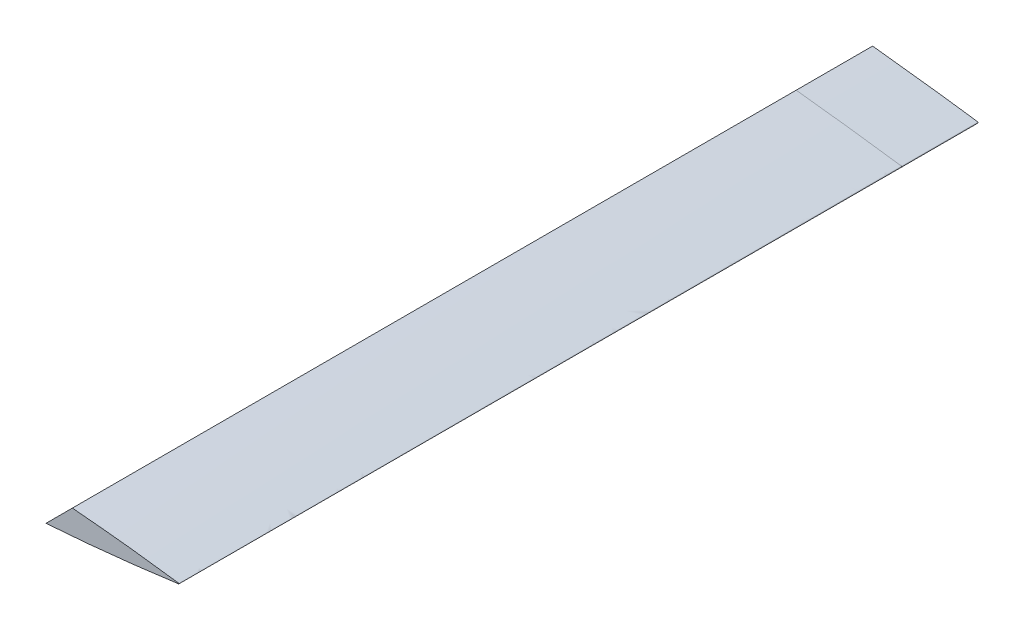
SolidWorks part; units mm, degrees
ref_plane "Front Plane" through (0, 0, 0) normal (1, 0, 0) x (0, 1, 0)
ref_plane "Top Plane" through (0, 0, 0) normal (0, 0, 1) x (0, 1, 0)
ref_plane "Right Plane" through (0, 0, 0) normal (0, 1, 0) x (-1, 0, 0)
curve "Curve2"
  spline degree 3 poles (90, 0.1134, 0) (89.9538, 0.1199, 0) (89.7691, 0.1458, 0) (89.3547, 0.2036, 0) (88.6668, 0.299, 0) (87.7097, 0.43, 0) (86.4894, 0.595, 0) (85.0132, 0.7907, 0) (83.2903, 1.0144, 0) (81.3314, 1.2627, 0) (79.1484, 1.5322, 0) (76.7549, 1.8188, 0) (74.1657, 2.1193, 0) (71.3966, 2.4294, 0) (68.4648, 2.7453, 0) (65.3883, 3.0632, 0) (62.1861, 3.379, 0) (58.878, 3.6881, 0) (55.4843, 3.9866, 0) (52.026, 4.2695, 0) (48.5244, 4.5321, 0) (45.001, 4.7696, 0) (41.4775, 4.977, 0) (37.9757, 5.149, 0) (34.5172, 5.2811, 0) (31.1233, 5.369, 0) (27.8148, 5.4084, 0) (24.6121, 5.3961, 0) (21.5349, 5.3298, 0) (18.6023, 5.2078, 0) (15.8322, 5.0298, 0) (13.2417, 4.7963, 0) (10.8466, 4.5092, 0) (8.6616, 4.1708, 0) (6.6998, 3.7847, 0) (4.9728, 3.3553, 0) (3.4903, 2.8868, 0) (2.26, 2.3835, 0) (1.2857, 1.8489, 0) (0.569, 1.2818, 0) (0.1099, 0.6686, 0) (-0.0512, 0, 0) (0.1099, -0.6686, 0) (0.569, -1.2818, 0) (1.2857, -1.8489, 0) (2.26, -2.3835, 0) (3.4903, -2.8868, 0) (4.9728, -3.3553, 0) (6.6998, -3.7847, 0) (8.6616, -4.1708, 0) (10.8466, -4.5092, 0) (13.2417, -4.7963, 0) (15.8322, -5.0298, 0) (18.6023, -5.2078, 0) (21.5349, -5.3298, 0) (24.6121, -5.3961, 0) (27.8148, -5.4084, 0) (31.1233, -5.369, 0) (34.5172, -5.2811, 0) (37.9757, -5.149, 0) (41.4775, -4.977, 0) (45.001, -4.7696, 0) (48.5244, -4.5321, 0) (52.026, -4.2695, 0) (55.4843, -3.9866, 0) (58.878, -3.6881, 0) (62.1861, -3.379, 0) (65.3883, -3.0632, 0) (68.4648, -2.7453, 0) (71.3966, -2.4294, 0) (74.1657, -2.1193, 0) (76.7549, -1.8188, 0) (79.1484, -1.5322, 0) (81.3314, -1.2627, 0) (83.2903, -1.0144, 0) (85.0132, -0.7907, 0) (86.4894, -0.595, 0) (87.7097, -0.43, 0) (88.6668, -0.299, 0) (89.3547, -0.2036, 0) (89.7691, -0.1458, 0) (89.9538, -0.1199, 0) (90, -0.1134, 0) knots 0 0 0 0 0.000763 0.003048 0.006841 0.012116 0.018841 0.026973 0.03646 0.047243 0.059254 0.072417 0.086651 0.101866 0.117969 0.134858 0.152428 0.170572 0.189175 0.208122 0.227297 0.24658 0.265853 0.284997 0.303895 0.322433 0.340499 0.357984 0.374788 0.390812 0.405965 0.420162 0.433328 0.445394 0.456301 0.466004 0.474472 0.481696 0.487704 0.492583 0.496544 0.5 0.503456 0.507417 0.512296 0.518304 0.525528 0.533996 0.543699 0.554606 0.566672 0.579838 0.594035 0.609188 0.625212 0.642016 0.659501 0.677567 0.696105 0.715003 0.734147 0.75342 0.772703 0.791878 0.810825 0.829428 0.847572 0.865142 0.882031 0.898134 0.913349 0.927583 0.940746 0.952757 0.96354 0.973027 0.981159 0.987884 0.993159 0.996952 0.999237 1 1 1 1
sketch "Sketch2" plane through (0, 0, 0) normal (0, 0, 1) x (0, 1, 0)
  arc A0 (-0.1134, -90) -> (0.1134, -90) centre (0, -89.9841) ccw
  spline S0 degree 3 poles (1966.8421, -449.5678) (-10.9329, -144.6657) (-3.7009, -117.3601) (0.2036, -89.3547) (0.299, -88.6668) (0.43, -87.7097) (0.595, -86.4894) (0.7907, -85.0132) (1.0144, -83.2903) (1.2627, -81.3314) (1.5322, -79.1484) (1.8188, -76.7549) (2.1193, -74.1657) (2.4294, -71.3966) (2.7453, -68.4648) (3.0632, -65.3883) (3.379, -62.1861) (3.6881, -58.878) (3.9866, -55.4843) (4.2695, -52.026) (4.5321, -48.5244) (4.7696, -45.001) (4.977, -41.4775) (5.149, -37.9757) (5.2811, -34.5172) (5.369, -31.1233) (5.4084, -27.8148) (5.3961, -24.6121) (5.3298, -21.5349) (5.2078, -18.6023) (5.0298, -15.8322) (4.7963, -13.2417) (4.5092, -10.8466) (4.1708, -8.6616) (3.7847, -6.6998) (3.3553, -4.9728) (2.8868, -3.4903) (2.3835, -2.26) (1.8489, -1.2857) (1.2818, -0.569) (0.6686, -0.1099) (0, 0.0512) (-0.6686, -0.1099) (-1.2818, -0.569) (-1.8489, -1.2857) (-2.3835, -2.26) (-2.8868, -3.4903) (-3.3553, -4.9728) (-3.7847, -6.6998) (-4.1708, -8.6616) (-4.5092, -10.8466) (-4.7963, -13.2417) (-5.0298, -15.8322) (-5.2078, -18.6023) (-5.3298, -21.5349) (-5.3961, -24.6121) (-5.4084, -27.8148) (-5.369, -31.1233) (-5.2811, -34.5172) (-5.149, -37.9757) (-4.977, -41.4775) (-4.7696, -45.001) (-4.5321, -48.5244) (-4.2695, -52.026) (-3.9866, -55.4843) (-3.6881, -58.878) (-3.379, -62.1861) (-3.0632, -65.3883) (-2.7453, -68.4648) (-2.4294, -71.3966) (-2.1193, -74.1657) (-1.8188, -76.7549) (-1.5322, -79.1484) (-1.2627, -81.3314) (-1.0144, -83.2903) (-0.7907, -85.0132) (-0.595, -86.4894) (-0.43, -87.7097) (-0.299, -88.6668) (-0.2036, -89.3547) (3.7009, -117.36) (10.9329, -144.6654) (-1966.8144, -449.5636) knots -0.45542 -0.45542 -0.45542 -0.45542 0.000763 0.003048 0.006841 0.012116 0.018841 0.026973 0.03646 0.047243 0.059254 0.072417 0.086651 0.101866 0.117969 0.134858 0.152428 0.170572 0.189175 0.208122 0.227297 0.24658 0.265853 0.284997 0.303895 0.322433 0.340499 0.357984 0.374788 0.390812 0.405965 0.420162 0.433328 0.445394 0.456301 0.466004 0.474472 0.481696 0.487704 0.492583 0.496544 0.5 0.503456 0.507417 0.512296 0.518304 0.525528 0.533996 0.543699 0.554606 0.566672 0.579838 0.594035 0.609188 0.625212 0.642016 0.659501 0.677567 0.696105 0.715003 0.734147 0.75342 0.772703 0.791878 0.810825 0.829428 0.847572 0.865142 0.882031 0.898134 0.913349 0.927583 0.940746 0.952757 0.96354 0.973027 0.981159 0.987884 0.993159 0.996952 0.999237 1.455418 1.455418 1.455418 1.455418 only from (0.1134, -90) to (-0.1134, -90) construction
  spline S1 degree 3 poles (0.1134, -90) (0.1199, -89.9538) (0.1458, -89.7691) (0.2036, -89.3547) (0.299, -88.6668) (0.43, -87.7097) (0.595, -86.4894) (0.7907, -85.0132) (1.0144, -83.2903) (1.2627, -81.3314) (1.5322, -79.1484) (1.8188, -76.7549) (2.1193, -74.1657) (2.4294, -71.3966) (2.7453, -68.4648) (3.0632, -65.3883) (3.379, -62.1861) (3.6881, -58.878) (3.9866, -55.4843) (4.2695, -52.026) (4.5321, -48.5244) (4.7696, -45.001) (4.977, -41.4775) (5.149, -37.9757) (5.2811, -34.5172) (5.369, -31.1233) (5.4084, -27.8148) (5.3961, -24.6121) (5.3298, -21.5349) (5.2078, -18.6023) (5.0298, -15.8322) (4.7963, -13.2417) (4.5092, -10.8466) (4.1708, -8.6616) (3.7847, -6.6998) (3.3553, -4.9728) (2.8868, -3.4903) (2.3835, -2.26) (1.8489, -1.2857) (1.2818, -0.569) (0.6686, -0.1099) (0, 0.0512) (-0.6686, -0.1099) (-1.2818, -0.569) (-1.8489, -1.2857) (-2.3835, -2.26) (-2.8868, -3.4903) (-3.3553, -4.9728) (-3.7847, -6.6998) (-4.1708, -8.6616) (-4.5092, -10.8466) (-4.7963, -13.2417) (-5.0298, -15.8322) (-5.2078, -18.6023) (-5.3298, -21.5349) (-5.3961, -24.6121) (-5.4084, -27.8148) (-5.369, -31.1233) (-5.2811, -34.5172) (-5.149, -37.9757) (-4.977, -41.4775) (-4.7696, -45.001) (-4.5321, -48.5244) (-4.2695, -52.026) (-3.9866, -55.4843) (-3.6881, -58.878) (-3.379, -62.1861) (-3.0632, -65.3883) (-2.7453, -68.4648) (-2.4294, -71.3966) (-2.1193, -74.1657) (-1.8188, -76.7549) (-1.5322, -79.1484) (-1.2627, -81.3314) (-1.0144, -83.2903) (-0.7907, -85.0132) (-0.595, -86.4894) (-0.43, -87.7097) (-0.299, -88.6668) (-0.2036, -89.3547) (-0.1458, -89.7691) (-0.1199, -89.9538) (-0.1134, -90) knots 0 0 0 0 0.000763 0.003048 0.006841 0.012116 0.018841 0.026973 0.03646 0.047243 0.059254 0.072417 0.086651 0.101866 0.117969 0.134858 0.152428 0.170572 0.189175 0.208122 0.227297 0.24658 0.265853 0.284997 0.303895 0.322433 0.340499 0.357984 0.374788 0.390812 0.405965 0.420162 0.433328 0.445394 0.456301 0.466004 0.474472 0.481696 0.487704 0.492583 0.496544 0.5 0.503456 0.507417 0.512296 0.518304 0.525528 0.533996 0.543699 0.554606 0.566672 0.579838 0.594035 0.609188 0.625212 0.642016 0.659501 0.677567 0.696105 0.715003 0.734147 0.75342 0.772703 0.791878 0.810825 0.829428 0.847572 0.865142 0.882031 0.898134 0.913349 0.927583 0.940746 0.952757 0.96354 0.973027 0.981159 0.987884 0.993159 0.996952 0.999237 1 1 1 1
curve "Curve3"
  spline degree 3 poles (45, 0.0567, 0) (44.9912, 0.0579, 0) (44.9562, 0.0628, 0) (44.8775, 0.0739, 0) (44.7466, 0.0922, 0) (44.5636, 0.1176, 0) (44.3292, 0.15, 0) (44.0438, 0.1892, 0) (43.708, 0.2349, 0) (43.3227, 0.2868, 0) (42.8888, 0.3447, 0) (42.4073, 0.4081, 0) (41.8793, 0.4768, 0) (41.306, 0.5503, 0) (40.6888, 0.6281, 0) (40.0291, 0.71, 0) (39.3285, 0.7954, 0) (38.5885, 0.884, 0) (37.811, 0.9753, 0) (36.9978, 1.0688, 0) (36.1506, 1.1641, 0) (35.2716, 1.2607, 0) (34.3628, 1.3582, 0) (33.4263, 1.4561, 0) (32.4642, 1.554, 0) (31.4789, 1.6513, 0) (30.4726, 1.7476, 0) (29.4476, 1.8424, 0) (28.4065, 1.935, 0) (27.3515, 2.0251, 0) (26.2853, 2.112, 0) (25.2101, 2.1952, 0) (24.1287, 2.2742, 0) (23.0434, 2.3482, 0) (21.9569, 2.4169, 0) (20.8717, 2.4795, 0) (19.7902, 2.5354, 0) (18.7151, 2.5842, 0) (17.6488, 2.6253, 0) (16.5938, 2.6582, 0) (15.5526, 2.6822, 0) (14.5276, 2.6971, 0) (13.5213, 2.7024, 0) (12.5359, 2.6978, 0) (11.5738, 2.6829, 0) (10.6371, 2.6576, 0) (9.7282, 2.6217, 0) (8.8491, 2.5751, 0) (8.0019, 2.5179, 0) (7.1884, 2.45, 0) (6.4108, 2.3718, 0) (5.6707, 2.2834, 0) (4.9698, 2.1851, 0) (4.3099, 2.0772, 0) (3.6923, 1.9603, 0) (3.1187, 1.8346, 0) (2.5902, 1.7008, 0) (2.108, 1.5593, 0) (1.6732, 1.4107, 0) (1.2869, 1.2554, 0) (0.9496, 1.0939, 0) (0.662, 0.9266, 0) (0.4245, 0.7537, 0) (0.2376, 0.5749, 0) (0.1017, 0.3898, 0) (0.0185, 0.1974, 0) (-0.009, 0, 0) (0.0185, -0.1974, 0) (0.1017, -0.3898, 0) (0.2376, -0.5749, 0) (0.4245, -0.7537, 0) (0.662, -0.9266, 0) (0.9496, -1.0939, 0) (1.2869, -1.2554, 0) (1.6732, -1.4107, 0) (2.108, -1.5593, 0) (2.5902, -1.7008, 0) (3.1187, -1.8346, 0) (3.6923, -1.9603, 0) (4.3099, -2.0772, 0) (4.9698, -2.1851, 0) (5.6707, -2.2834, 0) (6.4108, -2.3718, 0) (7.1884, -2.45, 0) (8.0019, -2.5179, 0) (8.8491, -2.5751, 0) (9.7282, -2.6217, 0) (10.6371, -2.6576, 0) (11.5738, -2.6829, 0) (12.5359, -2.6978, 0) (13.5213, -2.7024, 0) (14.5276, -2.6971, 0) (15.5526, -2.6822, 0) (16.5938, -2.6582, 0) (17.6488, -2.6253, 0) (18.7151, -2.5842, 0) (19.7902, -2.5354, 0) (20.8717, -2.4795, 0) (21.9569, -2.4169, 0) (23.0434, -2.3482, 0) (24.1287, -2.2742, 0) (25.2101, -2.1952, 0) (26.2853, -2.112, 0) (27.3515, -2.0251, 0) (28.4065, -1.935, 0) (29.4476, -1.8424, 0) (30.4726, -1.7476, 0) (31.4789, -1.6513, 0) (32.4642, -1.554, 0) (33.4263, -1.4561, 0) (34.3628, -1.3582, 0) (35.2716, -1.2607, 0) (36.1506, -1.1641, 0) (36.9978, -1.0688, 0) (37.811, -0.9753, 0) (38.5885, -0.884, 0) (39.3285, -0.7954, 0) (40.0291, -0.71, 0) (40.6888, -0.6281, 0) (41.306, -0.5503, 0) (41.8793, -0.4768, 0) (42.4073, -0.4081, 0) (42.8888, -0.3447, 0) (43.3227, -0.2868, 0) (43.708, -0.2349, 0) (44.0438, -0.1892, 0) (44.3292, -0.15, 0) (44.5636, -0.1176, 0) (44.7466, -0.0922, 0) (44.8775, -0.0739, 0) (44.9562, -0.0628, 0) (44.9912, -0.0579, 0) (45, -0.0567, 0) knots 0 0 0 0 0.000289 0.001156 0.002598 0.004612 0.007194 0.010336 0.014031 0.018271 0.023046 0.028343 0.03415 0.040454 0.047239 0.054489 0.062186 0.070314 0.078852 0.08778 0.097077 0.106722 0.116691 0.126961 0.137507 0.148306 0.159331 0.170557 0.181957 0.193504 0.205172 0.216932 0.228758 0.240621 0.252495 0.26435 0.276161 0.287898 0.299536 0.311047 0.322405 0.333584 0.344559 0.355306 0.3658 0.376018 0.385938 0.395538 0.404798 0.413699 0.422222 0.430349 0.438066 0.445357 0.452209 0.458611 0.464554 0.47003 0.475035 0.479569 0.483637 0.48725 0.490431 0.493219 0.495674 0.497891 0.5 0.502109 0.504326 0.506781 0.509569 0.51275 0.516363 0.520431 0.524965 0.52997 0.535446 0.541389 0.547791 0.554643 0.561934 0.569651 0.577778 0.586301 0.595202 0.604462 0.614062 0.623982 0.6342 0.644694 0.655441 0.666416 0.677595 0.688953 0.700464 0.712102 0.723839 0.73565 0.747505 0.759379 0.771242 0.783068 0.794828 0.806496 0.818043 0.829443 0.840669 0.851694 0.862493 0.873039 0.883309 0.893278 0.902923 0.91222 0.921148 0.929686 0.937814 0.945511 0.952761 0.959546 0.96585 0.971657 0.976954 0.981729 0.985969 0.989664 0.992806 0.995388 0.997402 0.998844 0.999711 1 1 1 1
ref_plane "Plane1" through (0, 0, 135) normal (0, 0, 1) x (0, 1, 0)
sketch "Sketch3" plane through (0, 0, 135) normal (0, 0, 1) x (0, 1, 0)
  arc A5 (-0.0567, -89.992) -> (0.0567, -89.992) centre (0, -89.9841) ccw
  spline S3 degree 3 poles (0.0567, -89.992) (0.0579, -89.9833) (0.0628, -89.9483) (0.0739, -89.8696) (0.1164, -89.5652) (0.1702, -89.1751) (0.2349, -88.7) (0.2868, -88.3148) (0.3447, -87.8809) (0.4081, -87.3993) (0.4768, -86.8713) (0.5503, -86.298) (0.6281, -85.6808) (0.71, -85.0211) (0.8601, -83.7902) (1.0118, -82.4964) (1.1641, -81.1427) (1.295, -79.9514) (1.4253, -78.7216) (1.5881, -77.1207) (1.751, -75.4464) (1.9058, -73.7406) (2.0557, -71.9851) (2.1692, -70.5581) (2.2742, -69.1207) (2.3482, -68.0355) (2.4169, -66.9489) (2.4795, -65.8637) (2.5354, -64.7822) (2.5842, -63.7071) (2.6253, -62.6408) (2.6582, -61.5858) (2.6822, -60.5446) (2.6971, -59.5197) (2.7024, -58.5133) (2.6978, -57.5279) (2.6829, -56.5658) (2.6576, -55.6292) (2.6217, -54.7202) (2.5751, -53.8411) (2.5179, -52.9939) (2.45, -52.1805) (2.3718, -51.4028) (2.2834, -50.6627) (2.1851, -49.9618) (2.0772, -49.3019) (1.9603, -48.6844) (1.8346, -48.1107) (1.7008, -47.5822) (1.5593, -47.1) (1.4107, -46.6653) (1.2554, -46.2789) (1.0939, -45.9416) (0.9266, -45.654) (0.7537, -45.4166) (0.5749, -45.2296) (0.3898, -45.0937) (0.1974, -45.0106) (0, -44.983) (-0.1974, -45.0106) (-0.3898, -45.0937) (-0.5749, -45.2296) (-0.7537, -45.4166) (-0.9266, -45.654) (-1.0939, -45.9416) (-1.2554, -46.2789) (-1.4107, -46.6653) (-1.5593, -47.1) (-1.7008, -47.5822) (-1.8346, -48.1107) (-1.9603, -48.6844) (-2.0772, -49.3019) (-2.1851, -49.9618) (-2.2834, -50.6627) (-2.3718, -51.4028) (-2.45, -52.1805) (-2.5179, -52.9939) (-2.5751, -53.8411) (-2.6217, -54.7202) (-2.6576, -55.6292) (-2.6829, -56.5658) (-2.6978, -57.5279) (-2.7024, -58.5133) (-2.6971, -59.5197) (-2.6822, -60.5446) (-2.6582, -61.5858) (-2.6253, -62.6408) (-2.5842, -63.7071) (-2.5354, -64.7822) (-2.4795, -65.8637) (-2.4169, -66.9489) (-2.3482, -68.0355) (-2.2742, -69.1207) (-2.1692, -70.5581) (-2.0557, -71.9851) (-1.9058, -73.7406) (-1.751, -75.4464) (-1.5577, -77.4334) (-1.3926, -79.0341) (-1.2607, -80.2637) (-1.1641, -81.1427) (-1.0396, -82.2493) (-0.9165, -83.3094) (-0.7954, -84.3205) (-0.71, -85.0211) (-0.6281, -85.6808) (-0.5503, -86.298) (-0.4768, -86.8713) (-0.4081, -87.3993) (-0.3447, -87.8809) (-0.2868, -88.3148) (-0.2115, -88.8735) (-0.1464, -89.3485) (-0.0922, -89.7386) (-0.0739, -89.8696) (-0.0628, -89.9483) (-0.0579, -89.9833) (-0.0567, -89.992) knots 0 0 0 0 0.000289 0.001156 0.002598 0.010336 0.014031 0.018271 0.023046 0.028343 0.03415 0.040454 0.047239 0.054489 0.062186 0.08778 0.097077 0.106722 0.126961 0.137507 0.159331 0.181957 0.193504 0.216932 0.228758 0.240621 0.252495 0.26435 0.276161 0.287898 0.299536 0.311047 0.322405 0.333584 0.344559 0.355306 0.3658 0.376018 0.385938 0.395538 0.404798 0.413699 0.422222 0.430349 0.438066 0.445357 0.452209 0.458611 0.464554 0.47003 0.475035 0.479569 0.483637 0.48725 0.490431 0.493219 0.495674 0.497891 0.5 0.502109 0.504326 0.506781 0.509569 0.51275 0.516363 0.520431 0.524965 0.52997 0.535446 0.541389 0.547791 0.554643 0.561934 0.569651 0.577778 0.586301 0.595202 0.604462 0.614062 0.623982 0.6342 0.644694 0.655441 0.666416 0.677595 0.688953 0.700464 0.712102 0.723839 0.73565 0.747505 0.759379 0.771242 0.783068 0.806496 0.818043 0.840669 0.862493 0.883309 0.893278 0.902923 0.91222 0.929686 0.937814 0.945511 0.952761 0.959546 0.96585 0.971657 0.976954 0.981729 0.985969 0.995388 0.997402 0.998844 0.999711 1 1 1 1
loft "Loft3" add profiles "Sketch2", "Sketch3"
sketch "Sketch4" plane through (0, 0, 0) normal (0, 0, -1) x (1, 0, 0)
  circle A0 centre (39.9841, 0) radius 3.175
  arc A3 (90, -0.1134) -> (90, 0.1134) centre (89.9841, 0) ccw
  arc A4 (90, -0.1134) -> (90, 0.1134) centre (89.9841, 0) ccw
  spline S4 degree 3 poles (2097.8875, -2141.6804) (81.2904, 65.0706) (-6.184, 7.7379) (0.5688, -1.2818) (1.2856, -1.8489) (2.2599, -2.3835) (3.4902, -2.8868) (4.9726, -3.3553) (6.6996, -3.7847) (8.6614, -4.1708) (10.8465, -4.5092) (13.2416, -4.7963) (15.8321, -5.0298) (18.6022, -5.2079) (21.5348, -5.3299) (24.6119, -5.3961) (27.8146, -5.4084) (31.1231, -5.369) (34.5171, -5.2811) (37.9756, -5.149) (41.4774, -4.977) (45.0009, -4.7696) (48.5243, -4.5321) (52.026, -4.2695) (55.4843, -3.9866) (58.878, -3.6881) (62.1861, -3.379) (65.3883, -3.0632) (68.4648, -2.7453) (71.3966, -2.4294) (74.1657, -2.1193) (76.7549, -1.8188) (79.1484, -1.5322) (81.3313, -1.2627) (83.2903, -1.0144) (85.0132, -0.7907) (86.4894, -0.595) (87.7097, -0.43) (88.6668, -0.299) (89.3547, -0.2036) (121.3566, 4.2581) (152.5138, 13.0837) (600.1044, -2955.3731) knots -0.168575 -0.168575 -0.168575 -0.168575 0.003456 0.007417 0.012296 0.018304 0.025528 0.033996 0.043699 0.054606 0.066672 0.079838 0.094035 0.109188 0.125212 0.142016 0.159501 0.177567 0.196105 0.215003 0.234147 0.25342 0.272703 0.291878 0.310825 0.329428 0.347572 0.365142 0.382031 0.398134 0.413349 0.427583 0.440746 0.452757 0.46354 0.473027 0.481159 0.487884 0.493159 0.496952 0.499237 1.021387 1.021387 1.021387 1.021387 only from (-0.0002, 0) to (90, -0.1134)
  spline S5 degree 3 poles (260.8421, -2934.404) (598.8583, -252.7331) (351.7953, -32.5821) (78.6263, 1.6023) (72.9292, 2.2653) (67.2268, 2.8806) (62.4707, 3.3538) (58.6634, 3.7067) (55.8067, 3.9581) (52.9488, 4.195) (50.0896, 4.4164) (47.2292, 4.6211) (44.3675, 4.8074) (41.5046, 4.9736) (38.6405, 5.1171) (35.7752, 5.2356) (32.9088, 5.3262) (30.0417, 5.3852) (27.174, 5.4083) (24.3062, 5.3906) (21.917, 5.3367) (20.0065, 5.2661) (18.5742, 5.1983) (17.1428, 5.1142) (15.7125, 5.0123) (14.2838, 4.8906) (12.8571, 4.7469) (11.4331, 4.5785) (10.0127, 4.3816) (8.5973, 4.1517) (7.4235, 3.9274) (6.4895, 3.7238) (5.7921, 3.5576) (5.0986, 3.3755) (4.41, 3.1758) (3.7279, 2.9545) (3.0547, 2.7077) (2.3937, 2.429) (1.7518, 2.1091) (1.1389, 1.7346) (0.5816, 1.2805) (-6.4398, -7.5194) (75.7669, -67.508) (2215.6517, 2017.9535) knots -3.89743 -3.89743 -3.89743 -3.89743 0.532086 0.56328 0.594474 0.625669 0.656863 0.67246 0.688057 0.703654 0.719251 0.734849 0.750446 0.766043 0.78164 0.797237 0.812834 0.828431 0.844029 0.859626 0.875223 0.883021 0.89082 0.898619 0.906417 0.914216 0.922014 0.929813 0.937611 0.94541 0.953209 0.957108 0.961007 0.964906 0.968806 0.972705 0.976604 0.980504 0.984403 0.988302 0.992201 0.996101 1.170104 1.170104 1.170104 1.170104 only from (90, 0.1134) to (-0.0002, 0)
  spline S6 degree 3 poles (-0.0002, 0) (-0.0002, -0.2126) (0.1097, -0.6686) (0.5688, -1.2818) (1.2856, -1.8489) (2.2599, -2.3835) (3.4902, -2.8868) (4.9726, -3.3553) (6.6996, -3.7847) (8.6614, -4.1708) (10.8465, -4.5092) (13.2416, -4.7963) (15.8321, -5.0298) (18.6022, -5.2079) (21.5348, -5.3299) (24.6119, -5.3961) (27.8146, -5.4084) (31.1231, -5.369) (34.5171, -5.2811) (37.9756, -5.149) (41.4774, -4.977) (45.0009, -4.7696) (48.5243, -4.5321) (52.026, -4.2695) (55.4843, -3.9866) (58.878, -3.6881) (62.1861, -3.379) (65.3883, -3.0632) (68.4648, -2.7453) (71.3966, -2.4294) (74.1657, -2.1193) (76.7549, -1.8188) (79.1484, -1.5322) (81.3313, -1.2627) (83.2903, -1.0144) (85.0132, -0.7907) (86.4894, -0.595) (87.7097, -0.43) (88.6668, -0.299) (89.3547, -0.2036) (89.7691, -0.1458) (89.9538, -0.1199) (90, -0.1134) knots 0 0 0 0 0.003456 0.007417 0.012296 0.018304 0.025528 0.033996 0.043699 0.054606 0.066672 0.079838 0.094035 0.109188 0.125212 0.142016 0.159501 0.177567 0.196105 0.215003 0.234147 0.25342 0.272703 0.291878 0.310825 0.329428 0.347572 0.365142 0.382031 0.398134 0.413349 0.427583 0.440746 0.452757 0.46354 0.473027 0.481159 0.487884 0.493159 0.496952 0.499237 0.5 0.5 0.5 0.5
  spline S7 degree 3 poles (90, 0.1134) (88.1067, 0.3789) (84.3174, 0.8901) (78.6263, 1.6023) (72.9292, 2.2653) (67.2268, 2.8806) (62.4707, 3.3538) (58.6634, 3.7067) (55.8067, 3.9581) (52.9488, 4.195) (50.0896, 4.4164) (47.2292, 4.6211) (44.3675, 4.8074) (41.5046, 4.9736) (38.6405, 5.1171) (35.7752, 5.2356) (32.9088, 5.3262) (30.0417, 5.3852) (27.174, 5.4083) (24.3062, 5.3906) (21.917, 5.3367) (20.0065, 5.2661) (18.5742, 5.1983) (17.1428, 5.1142) (15.7125, 5.0123) (14.2838, 4.8906) (12.8571, 4.7469) (11.4331, 4.5785) (10.0127, 4.3816) (8.5973, 4.1517) (7.4235, 3.9274) (6.4895, 3.7238) (5.7921, 3.5576) (5.0986, 3.3755) (4.41, 3.1758) (3.7279, 2.9545) (3.0547, 2.7077) (2.3937, 2.429) (1.7518, 2.1091) (1.1389, 1.7346) (0.5816, 1.2805) (0.1299, 0.7143) (-0.0002, 0.2381) (-0.0002, 0) knots 0.500891 0.500891 0.500891 0.500891 0.532086 0.56328 0.594474 0.625669 0.656863 0.67246 0.688057 0.703654 0.719251 0.734849 0.750446 0.766043 0.78164 0.797237 0.812834 0.828431 0.844029 0.859626 0.875223 0.883021 0.89082 0.898619 0.906417 0.914216 0.922014 0.929813 0.937611 0.94541 0.953209 0.957108 0.961007 0.964906 0.968806 0.972705 0.976604 0.980504 0.984403 0.988302 0.992201 0.996101 1 1 1 1
  dimension "D2" = 6.35
  dimension "D3" = 50
  dimension "D1" = 0
extrude "Cut-Extrude3" cut sketch "Sketch4" against normal blind 40 contours A0
sketch "Sketch7" plane through (0, 0, 0) normal (0, 1, 0) x (-1, 0, 0)
  line L0 (-44.9916, 135) -> (-89.992, 135) construction
  line L1 (-67.4918, 135) -> (-97.4918, 135)
  line L2 (-67.4918, 135) -> (-67.4918, 15)
  line L3 (-67.4918, 15) -> (-97.4918, 15)
  line L4 (-97.4918, 135) -> (-97.4918, 15)
  line L6 (-67.4918, 135) -> (8.8995, 135)
  line L7 (-67.4918, 135) -> (-67.4918, 0)
  line L8 (-67.4918, 0) -> (8.8995, 0)
  line L9 (8.8995, 135) -> (8.8995, 0)
  line L10 (-97.4918, 15) -> (-67.4918, 15)
  line L11 (-97.4918, 15) -> (-97.4918, 0)
  line L12 (-97.4918, 0) -> (-67.4918, 0)
  line L13 (-67.4918, 15) -> (-67.4918, 0)
  dimension "D1" = 30
  dimension "D2" = 120
extrude "Cut-Extrude6" cut sketch "Sketch7" against normal through all both and the other way through all contours L7 L6 L9 L8 | L11 L10 L13 L12
sketch "Sketch8" plane through (0, 0, 15) normal (0, 0, -1) x (1, 0, 0)
  line L0 (67.4918, 2.8159) -> (67.4918, -5.7915)
  line L1 (67.4918, -5.7915) -> (76.0992, -5.7915)
  line L2 (76.0992, -5.7915) -> (67.4918, 2.8159)
  dimension "D1" = 45
extrude "Cut-Extrude8" cut sketch "Sketch8" against normal through all
sketch "Sketch9" plane through (0, 0, 15) normal (0, 0, -1) x (1, 0, 0)
  line L0 (72.5833, -2.2756) -> (67.4918, 2.8159) construction
  line L1 (72.5833, -2.2756) -> (67.4918, 2.8159)
  spline S0 degree 3 poles (-807.0477, -2797.2882) (-509.9549, -120.5036) (-209.4137, 32.707) (73.8767, 2.1394) (79.2572, 1.5133) (84.6322, 0.8407) (88.211, 0.3579) (90.0247, 0.1035) (90.073, 0.0774) (90.1019, -0.0001) (90.073, -0.0773) (90.0247, -0.1035) (88.211, -0.3579) (84.6322, -0.8407) (79.2572, -1.5133) (-691.1569, -91.1684) (-1614.4001, 1197.8142) (2567.9148, 816.3937) knots -3.984992 -3.984992 -3.984992 -3.984992 0.875223 0.906417 0.937611 0.968806 1 1 1.000446 1.000891 1.001337 1.001783 1.001783 1.032977 1.064172 1.095366 14.432669 14.432669 14.432669 14.432669 only from (67.4918, 2.8159) to (72.5833, -2.2756) construction
  spline S1 degree 3 poles (67.4918, 2.8159) (67.8247, 2.7819) (69.9536, 2.5628) (73.8767, 2.1394) (79.2572, 1.5133) (84.6322, 0.8407) (88.211, 0.3579) (90.0247, 0.1035) (90.073, 0.0774) (90.1019, -0.0001) (90.073, -0.0773) (90.0247, -0.1035) (88.211, -0.3579) (84.6322, -0.8407) (79.2572, -1.5133) (75.2396, -1.9808) (73.0142, -2.2281) (72.5833, -2.2756) knots 0.869442 0.869442 0.869442 0.869442 0.875223 0.906417 0.937611 0.968806 1 1 1.000446 1.000891 1.001337 1.001783 1.001783 1.032977 1.064172 1.095366 1.102855 1.102855 1.102855 1.102855
extrude "Boss-Extrude1" add sketch "Sketch9" along normal blind 12.7
